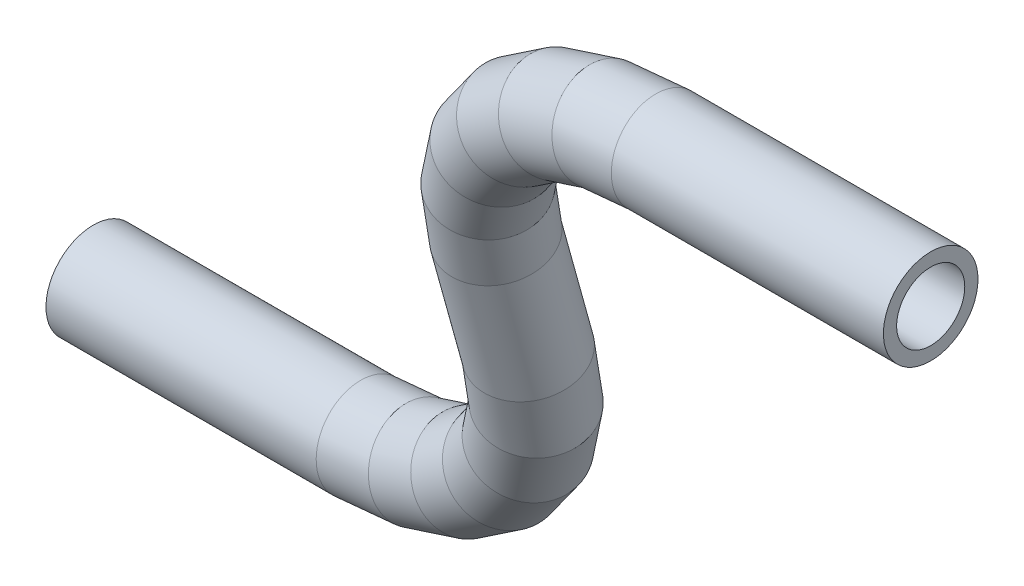
SolidWorks part; units mm, degrees
ref_plane "Front Plane" through (0, 0, 0) normal (0, 0, 1) x (1, 0, 0)
ref_plane "Top Plane" through (0, 0, 0) normal (0, 1, 0) x (1, 0, 0)
ref_plane "Right Plane" through (0, 0, 0) normal (1, 0, 0) x (0, 0, -1)
sketch3d "Path"
  line L0 (-2080.988, -26.6976, -19.3969) -> (-2099.188, -26.6976, -19.3969)
  line L1 (-2099.188, -26.6976, -19.3969) -> (-2103.0702, -27.1901, -19.5335)
  line L2 (-2103.0702, -27.1901, -19.5335) -> (-2106.688, -28.6341, -19.9338)
  line L3 (-2106.688, -28.6341, -19.9338) -> (-2109.7946, -30.9313, -20.5706)
  line L4 (-2109.7946, -30.9313, -20.5706) -> (-2112.1783, -33.925, -21.4005)
  line L5 (-2112.1783, -33.925, -21.4005) -> (-2113.6768, -37.4112, -22.367)
  line L6 (-2113.6768, -37.4112, -22.367) -> (-2114.188, -41.1524, -23.4042)
  line L7 (-2114.188, -41.1524, -23.4042) -> (-2114.188, -48.9867, -25.576)
  line L8 (-2114.188, -48.9867, -25.576) -> (-2114.6991, -52.7279, -26.6132)
  line L9 (-2114.6991, -52.7279, -26.6132) -> (-2116.1976, -56.2141, -27.5797)
  line L10 (-2116.1976, -56.2141, -27.5797) -> (-2118.5814, -59.2078, -28.4096)
  line L11 (-2118.5814, -59.2078, -28.4096) -> (-2121.688, -61.505, -29.0464)
  line L12 (-2121.688, -61.505, -29.0464) -> (-2125.3057, -62.949, -29.4467)
  line L13 (-2125.3057, -62.949, -29.4467) -> (-2129.188, -63.4415, -29.5833)
  line L14 (-2129.188, -63.4415, -29.5833) -> (-2147.388, -63.4415, -29.5833)
ref_plane "Start Plane" through (-2080.988, 0, 0) normal (1, 0, 0) x (0, 0, -1)
sketch "Profile" plane through (-2080.988, 0, 0) normal (1, 0, 0) x (0, 0, -1)
  circle A0 centre (19.3969, -26.6976) radius 3.175
  circle A1 centre (19.3969, -26.6976) radius 2.286
sweep "Tube" add profiles "Profile" path "Path"
